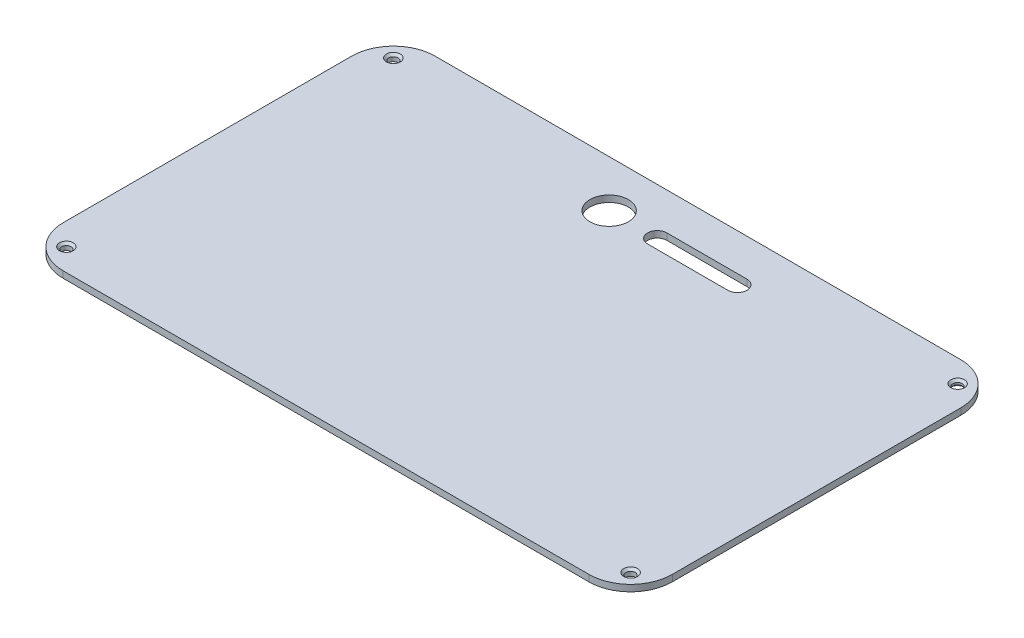
SolidWorks part; units mm, degrees
ref_plane "Front Plane" through (0, 0, 0) normal (0, 0, 1) x (1, 0, 0)
ref_plane "Top Plane" through (0, 0, 0) normal (0, 1, 0) x (1, 0, 0)
ref_plane "Right Plane" through (0, 0, 0) normal (1, 0, 0) x (0, 0, -1)
sketch "Sketch1" plane through (0, 0, 0) normal (0, 1, 0) x (1, 0, 0)
  line L1 (-82, -58) -> (82, -58)
  line L2 (-95, -45) -> (-95, 45)
  line L3 (-82, 58) -> (82, 58)
  line L4 (95, -45) -> (95, 45)
  line L5 (-95, -58) -> (95, 58) construction
  line L6 (-95, 58) -> (95, -58) construction
  arc A0 (-82, -58) -> (-95, -45) centre (-82, -45) cw
  arc A1 (82, -58) -> (95, -45) centre (82, -45) ccw
  arc A2 (82, 58) -> (95, 45) centre (82, 45) cw
  arc A3 (-95, 45) -> (-82, 58) centre (-82, 45) cw
  point P0 (0, 0)
  dimension "D3" = 13
  dimension "D1" = 190
  dimension "D2" = 116
extrude "Boss-Extrude1" add sketch "Sketch1" along normal mid plane 2.032
hole_wizard "Ø2.9 (2.9) Diameter Hole1" positions "Sketch2" profile "Sketch3" hole size "Ø2.9" standard "ANSI Metric" end condition through all
sketch "Sketch2" plane through (0, 1.016, 0) normal (0, 1, 0) x (1, 0, 0)
  line L0 (-95, 45) -> (-95, -45) construction
  line L1 (-82, -58) -> (82, -58) construction
  line L2 (0, 0) -> (-95, 0) construction
  line L4 (0, 0) -> (0, 58) construction
  line L5 (82, 58) -> (-82, 58) construction
  point P0 (-88, -51)
  point P20 (-88, 51)
  point P22 (88, -51)
  point P23 (88, 51)
  dimension "D1" = 7
  dimension "D2" = 7
sketch "Sketch3" plane through (-88, 1.016, 51) normal (1, 0, 0) x (0, 0, 1)
  line L0 (0, 0) -> (0, 2.032)
  line L1 (0, 2.032) -> (1.45, 2.032)
  line L2 (1.45, 2.032) -> (1.45, 0)
  line L5 (1.45, 0) -> (0, 0)
  line L11 (0, -6.35) -> (0, 107.95) construction
  dimension "Thru Hole Dia." = 2.9
  dimension "Thru Hole Depth" = 2.032
chamfer "Chamfer1" distance 0.7 angle 45 5 edges at (88, 1.016, -49.55) (88, -1.016, -49.55) (88, 1.016, 52.45) (-88, 1.016, -49.55) (-88, 1.016, 52.45)
sketch "Sketch4" plane through (0, 1.016, 0) normal (0, 1, 0) x (1, 0, 0)
  line L0 (82, 58) -> (-82, 58) construction
  line L1 (-95, 45) -> (-95, -45) construction
  circle A0 centre (-13.1, 43.4) radius 6
  dimension "D1" = 12
  dimension "D2" = 14.6
  dimension "D3" = 81.9
extrude "Cut-Extrude1" cut sketch "Sketch4" against normal through all
sketch "Sketch5" plane through (0, 1.016, 0) normal (0, 1, 0) x (1, 0, 0)
  line L0 (1.9, 43.4) -> (26.9, 43.4) construction
  line L1 (1.9, 46.4) -> (26.9, 46.4)
  line L2 (1.9, 40.4) -> (26.9, 40.4)
  line L3 (1.9, 43.4) -> (-13.1, 43.4) construction
  arc A0 (1.9, 46.4) -> (1.9, 40.4) centre (1.9, 43.4) ccw
  arc A1 (26.9, 40.4) -> (26.9, 46.4) centre (26.9, 43.4) ccw
  point P2 (14.4, 43.4)
  dimension "D1" = 6
  dimension "D2" = 25
  dimension "D3" = 15
extrude "Cut-Extrude2" cut sketch "Sketch5" against normal through all
